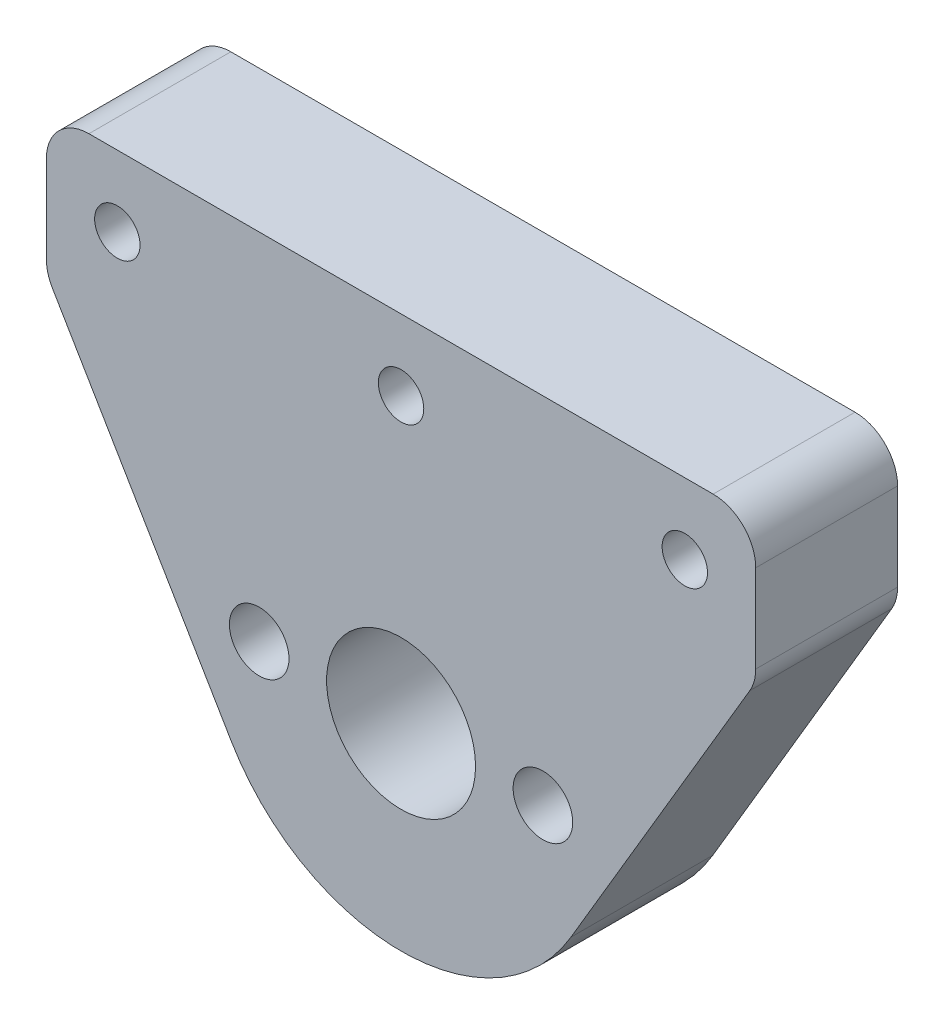
SolidWorks part; units mm, degrees
material "1060 合金"
ref_plane "正面" through (0, 0, 0) normal (0, 0, 1) x (1, 0, 0)
ref_plane "平面" through (0, 0, 0) normal (0, 1, 0) x (1, 0, 0)
ref_plane "右側面" through (0, 0, 0) normal (1, 0, 0) x (0, 0, -1)
sketch "ｽｹｯﾁ1" plane through (0, 0, 0) normal (0, 0, 1) x (1, 0, 0)
  line L0 (0, 0) -> (-20, 0) construction
  line L1 (0, 0) -> (0, -20) construction
  line L2 (-25, -5) -> (-11.969, -27.0677)
  line L3 (25, 5) -> (-25, 5)
  line L4 (25, 5) -> (25, -5)
  line L5 (25, -5) -> (-25, -5)
  line L6 (-25, 5) -> (-25, -5)
  line L7 (25, 5) -> (-25, -5) construction
  line L8 (25, -5) -> (-25, 5) construction
  line L9 (25, -5) -> (11.969, -27.0677)
  circle A0 centre (0, 0) radius 1.6
  circle A1 centre (-20, 0) radius 1.6
  circle A2 centre (0, -20) radius 13.9
  circle A3 centre (20, 0) radius 1.6
  circle A4 centre (0, -20) radius 10 construction
  circle A5 centre (-10, -20) radius 2.1
  circle A6 centre (10, -20) radius 2.1
  point P13 (-25, 0)
  dimension "D1" = 3.2
  dimension "D3" = 3.2
  dimension "D5" = 27.8
  dimension "D7" = 5
  dimension "D8" = 20
  dimension "D9" = 4.2
  dimension "D2" = 20
  dimension "D4" = 20
  dimension "D6" = 5
extrude "ﾎﾞｽ - 押し出し1" add sketch "ｽｹｯﾁ1" along normal blind 10 contours A2 A5 A6 | A2 L9 L5 L2 | L3 L6 L5 L4 A0 A1 A3
fillet "ﾌｨﾚｯﾄ1" radius 3 4 edges at (-25, -5, 5) (-25, 5, 5) (25, 5, 5) (25, -5, 5)
sketch "ｽｹｯﾁ2" plane through (0, 0, 10) normal (0, 0, 1) x (1, 0, 0)
  line L0 (-10, -20) -> (10, -20)
  circle A0 centre (0, -20) radius 5.25
  dimension "D1" = 10.5
extrude "ｶｯﾄ - 押し出し1" cut sketch "ｽｹｯﾁ2" against normal blind 10 contours L0 A0 | L0 A0
